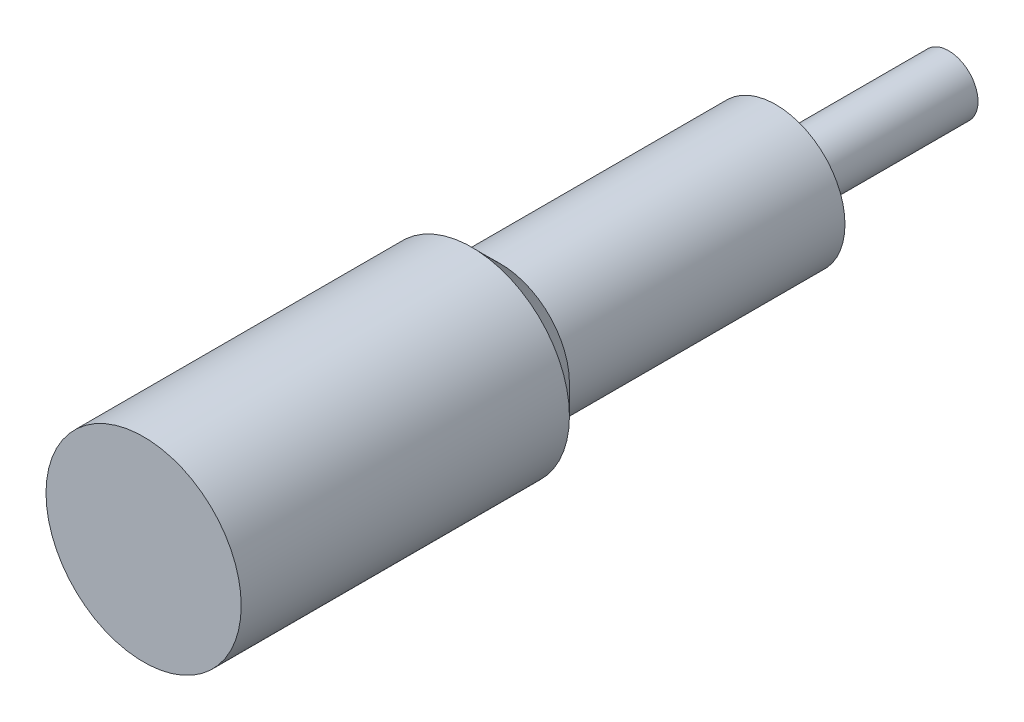
SolidWorks part; units mm, degrees
ref_plane "Front Plane" through (0, 0, 0) normal (0, 0, 1) x (1, 0, 0)
ref_plane "Top Plane" through (0, 0, 0) normal (0, 1, 0) x (1, 0, 0)
ref_plane "Right Plane" through (0, 0, 0) normal (1, 0, 0) x (0, 0, -1)
sketch "Sketch1" plane through (0, 0, 0) normal (1, 0, 0) x (0, 0, -1)
  line L0 (-15.0444, 0) -> (7.1544, 0) construction
  line L1 (-23.3, 0) -> (-23.3, 5.65)
  line L2 (-23.3, 5.65) -> (-4.3, 5.65)
  line L3 (-4.3, 5.65) -> (-2.65, 4)
  line L4 (-2.65, 4) -> (13.3, 4)
  line L5 (13.3, 4) -> (13.3, 1.7)
  line L6 (13.3, 1.7) -> (23.3, 1.7)
  line L7 (23.3, 1.7) -> (23.3, 0)
  line L8 (23.3, 0) -> (-23.3, 0)
  point P10 (0, 0)
  point P12 (0, 0)
  dimension "D1" = 11.3
  dimension "D2" = 8
  dimension "D3" = 3.4
  dimension "D4" = 19
  dimension "D5" = 36.6
  dimension "D6" = 45
  dimension "D7" = 10
revolve "Revolve1" add sketch "Sketch1" angle 360 about L0
